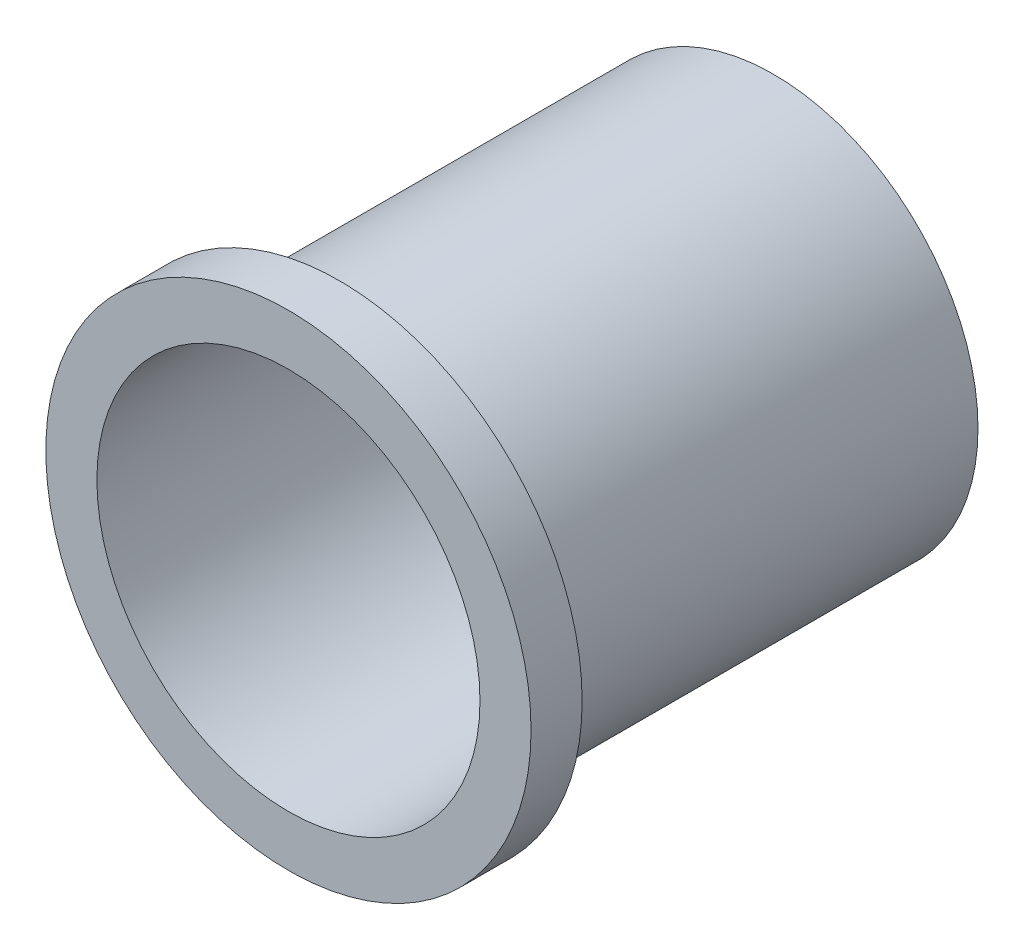
SolidWorks part; units mm, degrees
ref_plane "Front Plane" through (0, 0, 0) normal (0, 0, 1) x (1, 0, 0)
ref_plane "Top Plane" through (0, 0, 0) normal (0, 1, 0) x (1, 0, 0)
ref_plane "Right Plane" through (0, 0, 0) normal (1, 0, 0) x (0, 0, -1)
sketch "Sketch1" plane through (0, 0, 0) normal (0, 0, 1) x (1, 0, 0)
  circle A0 centre (0, 0) radius 80
  circle A1 centre (0, 0) radius 15
extrude "Boss-Extrude1" add sketch "Sketch1" along normal blind 20
sketch "Sketch2" plane through (0, 0, 20) normal (0, 0, 1) x (1, 0, 0)
  circle A0 centre (0, 0) radius 80
  circle A1 centre (0, 0) radius 75
extrude "Boss-Extrude2" add sketch "Sketch2" along normal blind 150
sketch "Sketch3" plane through (0, 0, 170) normal (0, 0, 1) x (1, 0, 0)
  circle A0 centre (0, 0) radius 75
  circle A1 centre (0, 0) radius 95
extrude "Boss-Extrude3" add sketch "Sketch3" along normal blind 20
fillet "Fillet1" radius 10 1 edges at (80, 0, 170)
